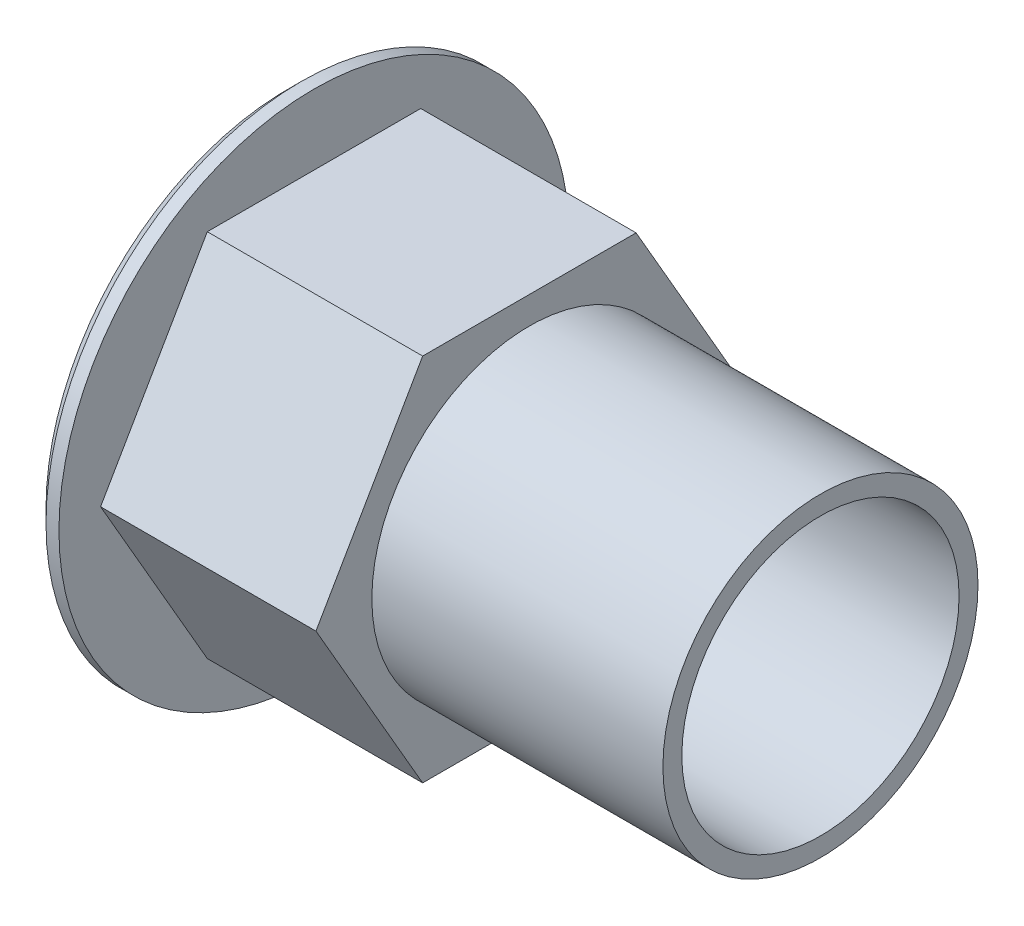
SolidWorks part; units mm, degrees
ref_plane "Front Plane" through (0, 0, 0) normal (0, 0, 1) x (1, 0, 0)
ref_plane "Top Plane" through (0, 0, 0) normal (0, 1, 0) x (1, 0, 0)
ref_plane "Right Plane" through (0, 0, 0) normal (1, 0, 0) x (0, 0, -1)
other "Configuration Table"
sketch "Sketch1" plane through (0, 0, 0) normal (0, 0, 1) x (1, 0, 0)
  line L0 (0, 0) -> (13.5536, 0) construction
  line L1 (0, 4.7625) -> (0, 8.3185)
  line L2 (0, 8.3185) -> (0.4445, 8.763)
  line L3 (0.4445, 8.763) -> (0.889, 8.763)
  line L4 (0.889, 8.763) -> (0.889, 5.4125)
  line L5 (0.889, 5.4125) -> (18.288, 5.4125)
  line L8 (18.288, 5.4125) -> (18.288, 4.7625)
  line L10 (0, 4.7625) -> (18.288, 4.7625)
  dimension "C" = 0.889
  dimension "A" = 17.399
  dimension "D3" = 135
  dimension "D4" = 0.4445
  dimension "B" = 16.637
  dimension "Hole dia" = 9.525
  dimension "D7" = 10.825
revolve "Revolve1" add sketch "Sketch1" angle 360 about L0
sketch "Sketch2" plane through (0.889, 0, 0) normal (1, 0, 0) x (0, 0, -1)
  line L1 (7.3323, 0) -> (3.6662, 6.35)
  line L2 (3.6662, 6.35) -> (-3.6662, 6.35)
  line L3 (-3.6662, 6.35) -> (-7.3323, 0)
  line L4 (-7.3323, 0) -> (-3.6662, -6.35)
  line L5 (-3.6662, -6.35) -> (3.6662, -6.35)
  line L6 (3.6662, -6.35) -> (7.3323, 0)
  circle A0 centre (0, 0) radius 6.35 construction
  circle A1 centre (0, 0) radius 5.4125 construction
  circle A2 centre (0, 0) radius 5.4125
  dimension "D" = 12.7
extrude "Extrude1" add sketch "Sketch2" along normal blind 7.399
surface "Surface-Offset1" [suppressed] parameters "D1"=0.254
equation "\"D1@Extrude1\" = \"A@Sketch1\"-(10/25.4)"
equation "\"D4@Sketch1\" = \"C@Sketch1\"/2"
equation "\"D7@Sketch1\" = \"Hole dia@Sketch1\"+(1.3/25.4)"
